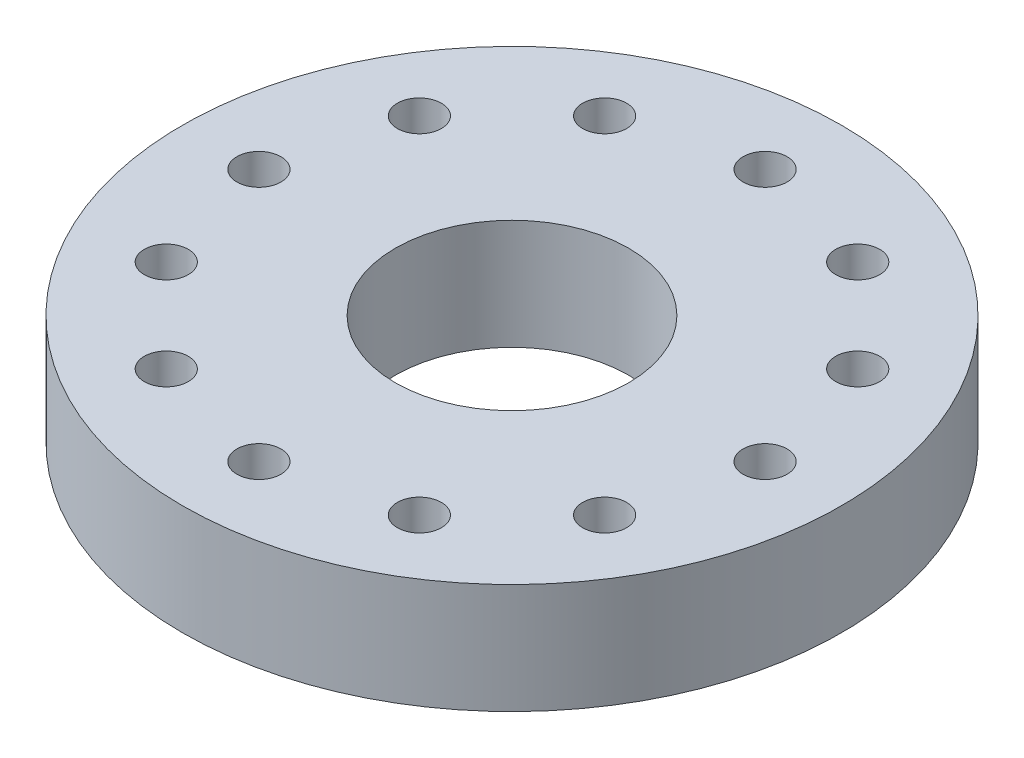
SolidWorks part; units mm, degrees
ref_plane "Front Plane" through (0, 0, 0) normal (0, 0, 1) x (1, 0, 0)
ref_plane "Top Plane" through (0, 0, 0) normal (0, 1, 0) x (1, 0, 0)
ref_plane "Right Plane" through (0, 0, 0) normal (1, 0, 0) x (0, 0, -1)
sketch "Sketch1" plane through (0, 0, 0) normal (0, 1, 0) x (1, 0, 0)
  circle A0 centre (0, 0) radius 29.95
  circle A1 centre (0, 0) radius 23 construction
  circle A2 centre (0, 23) radius 2
  circle A3 centre (11.5, 19.9186) radius 2
  circle A4 centre (19.9186, 11.5) radius 2
  circle A5 centre (23, 0) radius 2
  circle A6 centre (19.9186, -11.5) radius 2
  circle A7 centre (11.5, -19.9186) radius 2
  circle A8 centre (0, 0) radius 10.6
  circle A9 centre (0, -23) radius 2
  circle A10 centre (-11.5, -19.9186) radius 2
  circle A11 centre (-19.9186, -11.5) radius 2
  circle A12 centre (-23, 0) radius 2
  circle A13 centre (-19.9186, 11.5) radius 2
  circle A14 centre (-11.5, 19.9186) radius 2
  point P18 (0, 0)
  dimension "D1" = 46
  dimension "D2" = 4
  dimension "D4" = 59.9
  dimension "D5" = 21.2
  dimension "D3" = 12
extrude "Boss-Extrude1" add sketch "Sketch1" along normal blind 10
